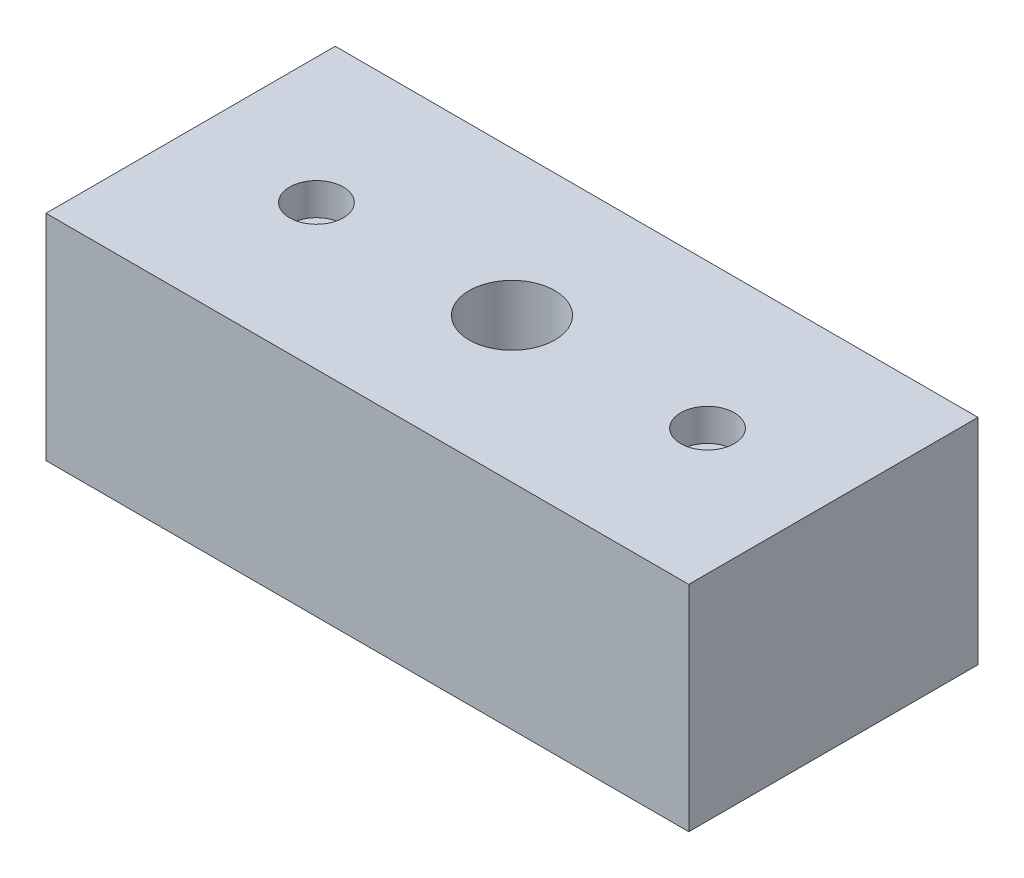
SolidWorks part; units mm, degrees
ref_plane "Front Plane" through (0, 0, 0) normal (0, 0, 1) x (1, 0, 0)
ref_plane "Top Plane" through (0, 0, 0) normal (0, 1, 0) x (1, 0, 0)
ref_plane "Right Plane" through (0, 0, 0) normal (1, 0, 0) x (0, 0, -1)
sketch "Sketch2" plane through (0, 0, 0) normal (0, 0, 1) x (1, 0, 0)
  line L1 (-30, -10) -> (30, -10)
  line L2 (-30, -10) -> (-30, 10)
  line L3 (-30, 10) -> (30, 10)
  line L4 (30, -10) -> (30, 10)
  line L5 (-30, -10) -> (30, 10) construction
  line L6 (-30, 10) -> (30, -10) construction
  point P0 (0, 0)
  dimension "D1" = 60
  dimension "D2" = 20
extrude "Boss-Extrude1" add sketch "Sketch2" along normal mid plane 27
sketch "Sketch3" plane through (0, 10, 0) normal (0, 1, 0) x (1, 0, 0)
  line L0 (-30, 0) -> (30, 0) construction
  line L1 (-30, -13.5) -> (-30, 13.5) construction
  line L2 (30, -13.5) -> (30, 13.5) construction
  line L3 (0, 13.5) -> (0, -13.5) construction
  line L4 (30, 13.5) -> (-30, 13.5) construction
  line L5 (30, -13.5) -> (-30, -13.5) construction
  circle A1 centre (-18.25, 0) radius 2.5
  circle A2 centre (18.25, 0) radius 2.5
  dimension "D2" = 5
  dimension "D3" = 36.5
extrude "Cut-Extrude1" cut sketch "Sketch3" against normal blind 3
sketch "Sketch4" plane through (0, 10, 0) normal (0, 1, 0) x (1, 0, 0)
  circle A0 centre (0, 0) radius 4
  dimension "D1" = 8
extrude "Cut-Extrude2" cut sketch "Sketch4" against normal through all
